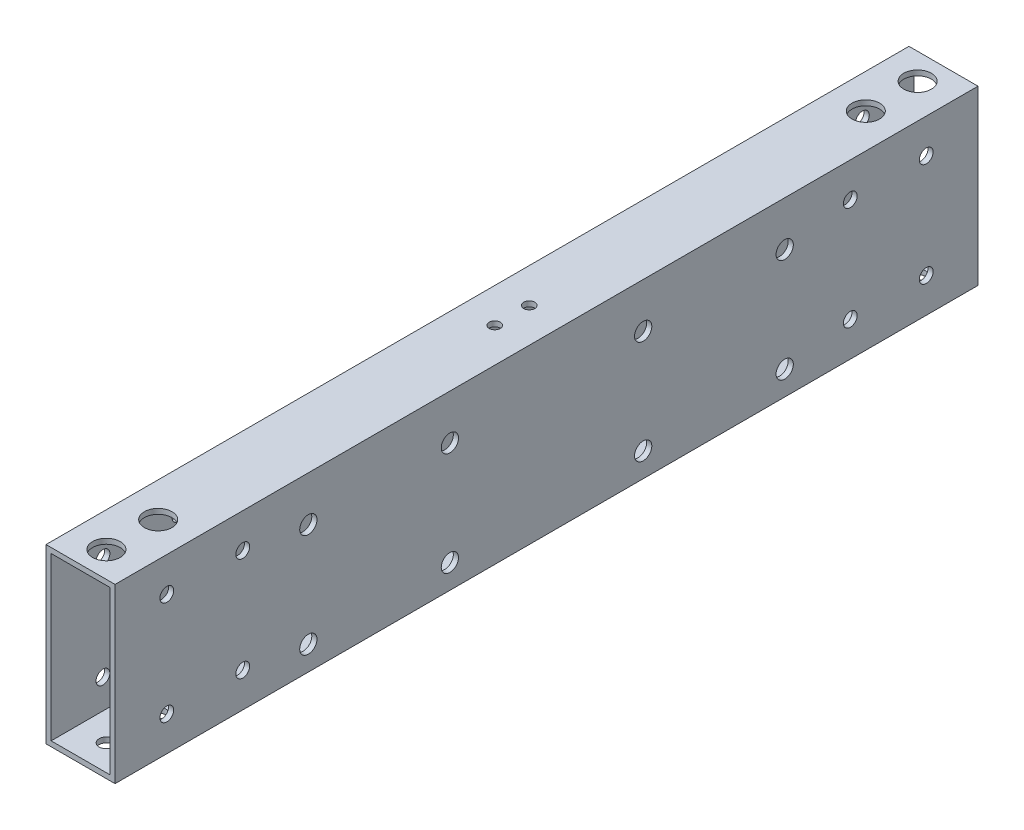
SolidWorks part; units mm, degrees
ref_plane "前视基准面" through (0, 0, 0) normal (0, 0, 1) x (1, 0, 0)
ref_plane "上视基准面" through (0, 0, 0) normal (0, 1, 0) x (1, 0, 0)
ref_plane "右视基准面" through (0, 0, 0) normal (1, 0, 0) x (0, 0, -1)
sketch "草图1" plane through (0, 0, 0) normal (0, 0, 1) x (1, 0, 0)
  line L0 (-8.5, 23.5) -> (8.5, 23.5)
  line L1 (-10, -25) -> (10, -25)
  line L2 (-10, -25) -> (-10, 25)
  line L3 (-10, 25) -> (10, 25)
  line L4 (10, -25) -> (10, 25)
  line L5 (-10, -25) -> (10, 25) construction
  line L6 (-10, 25) -> (10, -25) construction
  line L11 (8.5, -23.5) -> (8.5, 23.5)
  line L12 (-8.5, -23.5) -> (8.5, -23.5)
  line L13 (-8.5, -23.5) -> (-8.5, 23.5)
  point P9 (0, 0)
  dimension "D1" = 50
  dimension "D2" = 20
  dimension "D3" = 1.5
extrude "凸台-拉伸1" add sketch "草图1" against normal blind 250
sketch "草图2" plane through (-10, 0, 0) normal (-1, 0, 0) x (0, 0, 1)
  line L0 (-125, 20) -> (-125, -49980) construction
  line L1 (-250, 25) -> (0, 25) construction
  line L2 (-250, 25) -> (0, 25) construction
  line L11 (-56, -18) -> (-97, -18) construction
  line L13 (-56, -18) -> (-56, 12) construction
  line L14 (-56, 12) -> (-97, 12) construction
  line L15 (-97, -18) -> (-97, 12) construction
  line L16 (-56, -18) -> (-97, 12) construction
  line L17 (-56, 12) -> (-97, -18) construction
  line L18 (-71.3284, -3) -> (-50071.3284, -3) construction
  line L19 (-76.5, -3) -> (-76.5, 49997) construction
  line L20 (-194, 12) -> (-153, -18) construction
  line L21 (-194, -18) -> (-153, 12) construction
  line L22 (-153, -18) -> (-153, 12) construction
  line L23 (-194, 12) -> (-153, 12) construction
  line L24 (-194, -18) -> (-194, 12) construction
  line L25 (-194, -18) -> (-153, -18) construction
  line L26 (0, -25) -> (0, 25) construction
  circle A16 centre (-56, 12) radius 2.5
  circle A17 centre (-97, 12) radius 2.5
  circle A18 centre (-97, -18) radius 2.5
  circle A19 centre (-56, -18) radius 2.5
  circle A20 centre (-194, -18) radius 2.5
  circle A21 centre (-153, -18) radius 2.5
  circle A22 centre (-153, 12) radius 2.5
  circle A23 centre (-194, 12) radius 2.5
  point P4 (-125, 25)
  point P5 (-76.5, -3)
  point P28 (-173.5, -3)
  dimension "D4" = 5
  dimension "D5" = 76.5
  dimension "D2" = 41
  dimension "D1" = 30
  dimension "D3" = 28
extrude "切除-拉伸1" cut sketch "草图2" against normal through all
sketch "草图3" plane through (0, 25, 0) normal (0, 1, 0) x (1, 0, 0)
  line L0 (-10, 30) -> (49990, 30) construction
  line L2 (10, 0) -> (-10, 0) construction
  line L3 (0, 0) -> (0, 50000) construction
  line L4 (10, 125) -> (50010, 125) construction
  line L5 (10, 250) -> (10, 0) construction
  circle A0 centre (0, 22.5) radius 2.1
  circle A1 centre (0, 7.5) radius 2.1
  circle A2 centre (0, 242.5) radius 2.1
  circle A3 centre (0, 227.5) radius 2.1
  point P6 (0, 0)
  point P15 (10, 125)
  dimension "D2" = 4.2
  dimension "D3" = 4.2
  dimension "D1" = 30
  dimension "D4" = 15
  dimension "D5" = 7.5
extrude "切除-拉伸2" cut sketch "草图3" against normal through all
sketch "草图4" plane through (0, 25, 0) normal (0, 1, 0) x (1, 0, 0)
  line L0 (0, 250) -> (0, -49750) construction
  line L1 (10, 250) -> (-10, 250) construction
  line L2 (-10, 125) -> (49990, 125) construction
  line L3 (-10, 250) -> (-10, 0) construction
  circle A0 centre (0, 130) radius 1.6
  circle A1 centre (0, 120) radius 1.6
  point P4 (0, 250)
  point P9 (-10, 125)
  dimension "D1" = 3.2
  dimension "D2" = 10
extrude "切除-拉伸3" cut sketch "草图4" against normal blind 10
sketch "草图5" plane through (0, 25, 0) normal (0, 1, 0) x (1, 0, 0)
  line L0 (10, 125) -> (50010, 125) construction
  line L1 (10, 250) -> (10, 0) construction
  circle A0 centre (0, 22.5) radius 4
  circle A1 centre (0, 7.5) radius 4
  circle A2 centre (0, 242.5) radius 4
  circle A3 centre (0, 227.5) radius 4
  point P10 (10, 125)
  dimension "D1" = 8
  dimension "D2" = 8
extrude "切除-拉伸4" cut sketch "草图5" against normal blind 10
sketch "草图6" plane through (-10, 0, 0) normal (-1, 0, 0) x (0, 0, 1)
  line L0 (-125, 25) -> (-125, -75.8071) construction
  line L1 (-250, 25) -> (0, 25) construction
  circle A0 centre (-125, -4) radius 7.5
  dimension "D1" = 15
  dimension "D2" = 4
extrude "切除-拉伸5" cut sketch "草图6" against normal blind 10
sketch "草图7" plane through (-10, 0, 0) normal (-1, 0, 0) x (0, 0, 1)
  line L0 (-250, 0) -> (0, 0) construction
  line L1 (-250, 25) -> (-250, -25) construction
  line L2 (-125, 25) -> (-125, -25) construction
  line L3 (-250, 25) -> (0, 25) construction
  line L4 (-250, -25) -> (0, -25) construction
  line L5 (-250, 15) -> (0, 15) construction
  line L6 (0, 25) -> (0, -25) construction
  line L7 (-250, -15) -> (0, -15) construction
  circle A0 centre (-235, 15) radius 2
  circle A1 centre (-213, 15) radius 2
  circle A2 centre (-235, -15) radius 2
  circle A3 centre (-213, -15) radius 2
  circle A5 centre (-37, -15) radius 2
  circle A6 centre (-15, -15) radius 2
  circle A7 centre (-37, 15) radius 2
  circle A8 centre (-15, 15) radius 2
  dimension "D3" = 4
  dimension "D1" = 15
  dimension "D2" = 15
  dimension "D4" = 22
  dimension "D5" = 15
extrude "切除-拉伸6" cut sketch "草图7" against normal through all
equation "\"3。2\"=3.21956"
